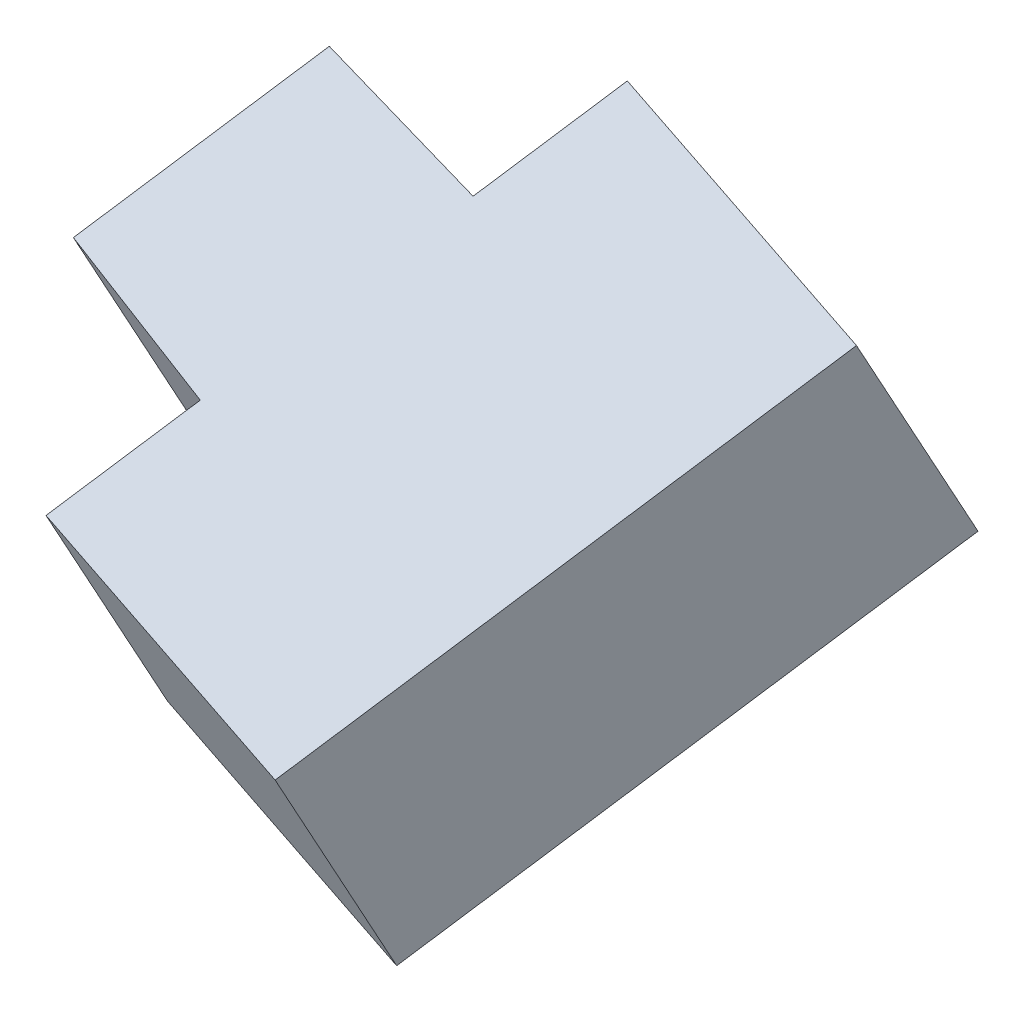
SolidWorks part; units mm, degrees
ref_plane "Front Plane" through (0, 0, 0) normal (0, 0, 1) x (1, 0, 0)
ref_plane "Top Plane" through (0, 0, 0) normal (0, 1, 0) x (1, 0, 0)
ref_plane "Right Plane" through (0, 0, 0) normal (1, 0, 0) x (0, 0, -1)
ref_plane "Plane1" through (-30.2839, 190.5651, 90.8517) normal (-0.142, 0.8935, 0.426) x (0.9896, 0.1388, 0.0388)
sketch "Sketch1" plane through (-30.2839, 190.5651, 90.8517) normal (-0.142, 0.8935, 0.426) x (0.9896, 0.1388, 0.0388)
  line L0 (1.5977, 170.7372) -> (2.9282, 174.8318) construction
  line L1 (1.5977, 170.7372) -> (2.9282, 174.8318) construction
  line L2 (8.5637, 165.1354) -> (10.2793, 164.578)
  line L3 (10.2793, 164.578) -> (5.8223, 150.8607)
  line L4 (5.8223, 150.8607) -> (-3.8404, 154.0003)
  line L5 (3.0479, 175.2002) -> (-23.3429, 93.9782) construction
  line L6 (3.0479, 175.2002) -> (-23.3429, 93.9782) construction
  line L7 (-3.8404, 154.0003) -> (-2.6578, 157.6401)
  line L8 (-2.6578, 157.6401) -> (-8.2994, 159.6935)
  line L9 (-8.2994, 159.6935) -> (-6.3371, 165.7327)
  line L10 (-6.3371, 165.7327) -> (-0.566, 164.0778)
  line L11 (-0.566, 164.0778) -> (0.6166, 167.7176)
  line L12 (0.6166, 167.7176) -> (8.5637, 165.1354)
  line L14 (-2.6585, 177.0543) -> (-29.0492, 95.8323) construction
  dimension "D1" = 92
  dimension "D2" = 6.35
  dimension "D3" = 3.8271
  dimension "D4" = 10.16
  dimension "D6" = 3.175
extrude "Boss-Extrude1" add sketch "Sketch1" along normal mid plane 6
